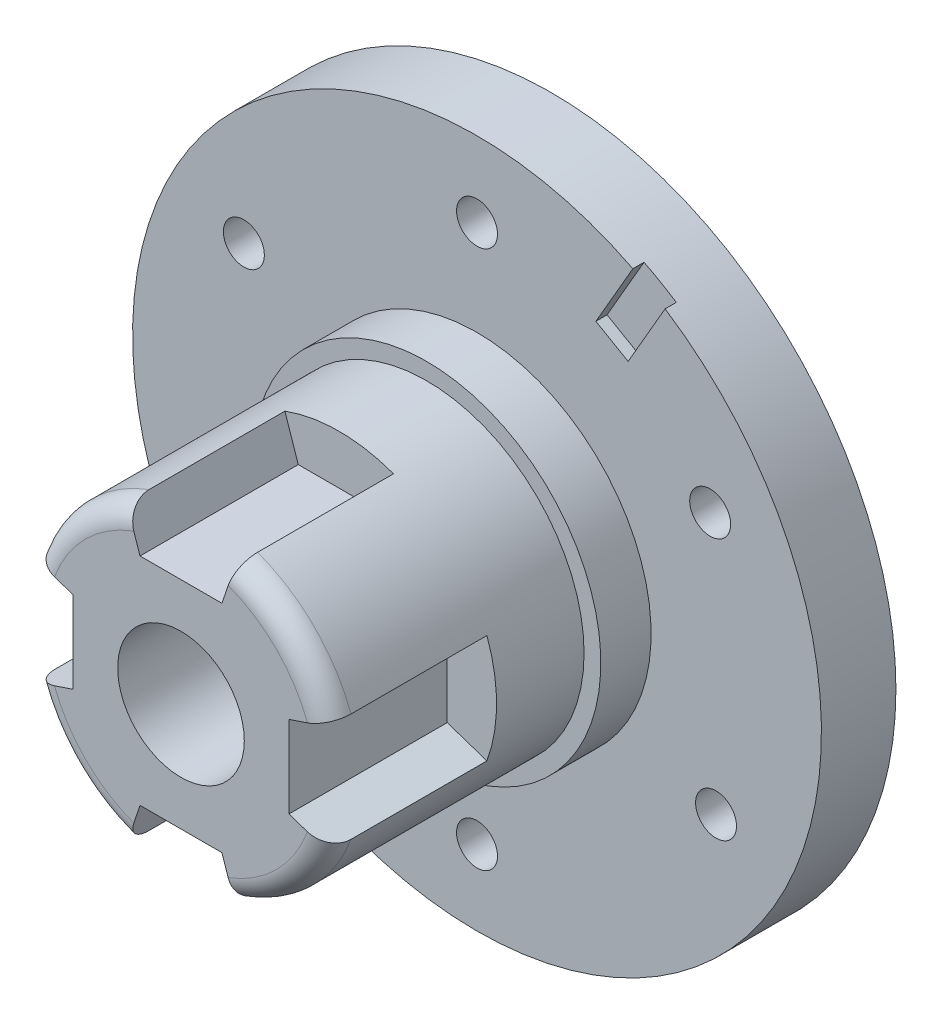
SolidWorks part; units mm, degrees
ref_plane "Спереди" through (0, 0, 0) normal (0, 0, 1) x (1, 0, 0)
ref_plane "Сверху" through (0, 0, 0) normal (0, 1, 0) x (1, 0, 0)
ref_plane "Справа" through (0, 0, 0) normal (1, 0, 0) x (0, 0, -1)
sketch "Эскиз1" plane through (0, 0, 0) normal (0, 0, 1) x (1, 0, 0)
  line L0 (0, 0) -> (0, 14.46) construction
  line L1 (0, 0) -> (-12.8378, -6.6545) construction
  line L2 (0, 0) -> (12.8378, -6.6545) construction
  circle A0 centre (0, 14.46) radius 1.1
  circle A1 centre (-12.8378, -6.6545) radius 1.1
  circle A2 centre (12.8378, -6.6545) radius 1.1
  circle A3 centre (0, 0) radius 18.5
  dimension "D4" = 2.2
  dimension "D5" = 37
  dimension "D1" = 14.46
  dimension "D2" = 117.4
  dimension "D3" = 117.4
extrude "Бобышка-Вытянуть1" add sketch "Эскиз1" along normal blind 4
sketch "Эскиз2" plane through (0, 0, 0) normal (0, 0, -1) x (-1, 0, 0)
  circle A0 centre (0, 14.46) radius 1.1
  circle A1 centre (12.8378, -6.6545) radius 1.1
  circle A2 centre (-12.8378, -6.6545) radius 1.1
  circle A3 centre (0, 14.46) radius 3
  circle A4 centre (12.8378, -6.6545) radius 3
  circle A5 centre (-12.8378, -6.6545) radius 3
  dimension "D1" = 2.2
  dimension "D2" = 6
extrude "Бобышка-Вытянуть2" [suppressed] add sketch "Эскиз2" along normal blind 1.2
sketch "Эскиз3" plane through (0, 0, 4) normal (0, 0, 1) x (1, 0, 0)
  circle A0 centre (0, 0) radius 8.45
  dimension "D1" = 16.9
extrude "Бобышка-Вытянуть3" add sketch "Эскиз3" along normal blind 15.9
fillet "Скругление1" radius 1.2 1 edges at (8.45, 0, 19.9)
sketch "Эскиз4" plane through (0, 0, 19.9) normal (0, 0, 1) x (1, 0, 0)
  line L0 (0, 0) -> (0, 5.8) construction
  line L1 (-2.2, 5.8) -> (-2.9319, 7.9784)
  line L2 (2.2, 5.8) -> (2.9319, 7.9784)
  line L3 (-2.2, 5.8) -> (2.2, 5.8)
  line L13 (5.8, 2.2) -> (7.9784, 2.9319)
  line L14 (5.8, -2.2) -> (7.9784, -2.9319)
  line L15 (5.8, 2.2) -> (5.8, -2.2)
  line L16 (0, 0) -> (5.8, 0) construction
  line L17 (2.2, -5.8) -> (2.9319, -7.9784)
  line L18 (-2.2, -5.8) -> (-2.9319, -7.9784)
  line L19 (2.2, -5.8) -> (-2.2, -5.8)
  line L20 (0, 0) -> (0, -5.8) construction
  line L21 (-5.8, -2.2) -> (-7.9784, -2.9319)
  line L22 (-5.8, 2.2) -> (-7.9784, 2.9319)
  line L23 (-5.8, -2.2) -> (-5.8, 2.2)
  line L24 (0, 0) -> (-5.8, 0) construction
  arc A0 (2.9319, 7.9784) -> (-2.9319, 7.9784) centre (0, 0) ccw
  arc A4 (7.9784, -2.9319) -> (7.9784, 2.9319) centre (0, 0) ccw
  arc A5 (-2.9319, -7.9784) -> (2.9319, -7.9784) centre (0, 0) ccw
  arc A6 (-7.9784, 2.9319) -> (-7.9784, -2.9319) centre (0, 0) ccw
  point P14 (5.0261, 2.6522)
  point P15 (5.0261, 2.6522)
  point P16 (-2.6522, 5.0261)
  point P19 (-2.6522, 5.0261)
  point P24 (2.6522, -5.0261)
  point P25 (2.6522, -5.0261)
  point P31 (-5.0261, -2.6522)
  point P32 (-5.0261, -2.6522)
  point P33 (0, 0)
  dimension "D1" = 17
  dimension "D2" = 4.4
  dimension "D3" = 108.571
  dimension "D4" = 5.8
  dimension "D5" = 37.141
  dimension "D6" = 4
extrude "Вырез-Вытянуть1" cut sketch "Эскиз4" against normal blind 8.5
sketch "Эскиз5" plane through (0, 0, 4) normal (0, 0, 1) x (1, 0, 0)
  circle A0 centre (0, 0) radius 9.35
  dimension "D1" = 18.7
extrude "Бобышка-Вытянуть4" add sketch "Эскиз5" along normal blind 2.7
sketch "Эскиз6" plane through (0, 0, 0) normal (0, 0, -1) x (-1, 0, 0)
  line L0 (0, 0) -> (0, -14.46) construction
  line L1 (0, 0) -> (12.5227, 7.23) construction
  line L2 (0, 0) -> (-12.5227, 7.23) construction
  circle A0 centre (-12.5227, 7.23) radius 1.1
  circle A1 centre (12.5227, 7.23) radius 1.1
  circle A2 centre (0, -14.46) radius 1.1
  dimension "D4" = 2.2
  dimension "D1" = 14.46
  dimension "D2" = 120
  dimension "D3" = 120
extrude "Вырез-Вытянуть2" cut sketch "Эскиз6" against normal through all
sketch "Эскиз7" plane through (0, 0, 19.9) normal (0, 0, 1) x (1, 0, 0)
  circle A0 centre (0, 0) radius 3.4
  dimension "D1" = 6.8
extrude "Вырез-Вытянуть3" cut sketch "Эскиз7" against normal blind 6.5
sketch "Эскиз8" plane through (0, 0, 0) normal (0, 0, 1) x (1, 0, 0)
  line L0 (0, 0) -> (0, 25.3988) construction
  line L1 (0, 0) -> (11.7334, 20.3229) construction
  line L3 (8.116, 12.0574) -> (10.116, 15.5215)
  line L4 (8.116, 12.0574) -> (6.384, 13.0574)
  line L5 (6.384, 13.0574) -> (8.384, 16.5215)
  line L6 (10.116, 15.5215) -> (8.384, 16.5215)
  line L7 (8.116, 12.0574) -> (8.384, 16.5215) construction
  line L8 (6.384, 13.0574) -> (10.116, 15.5215) construction
  point P3 (8.25, 14.2894)
  dimension "D1" = 30
  dimension "D2" = 2
  dimension "D3" = 4
  dimension "D4" = 16.5
extrude "Вырез-Вытянуть5" cut sketch "Эскиз8" against normal blind 0.6 from surface at 4 starting at face at (13.6227, 7.23, 4)
